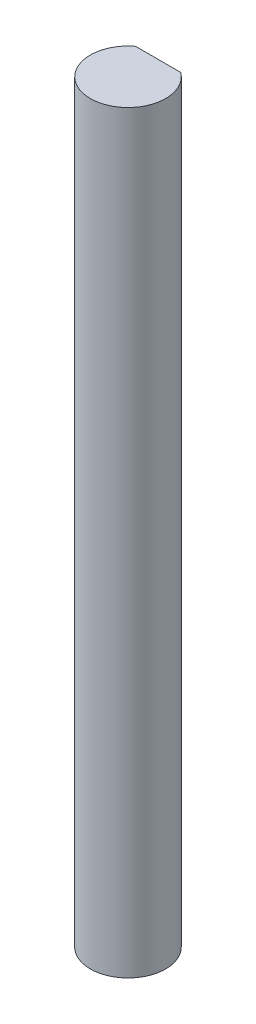
SolidWorks part; units mm, degrees
ref_plane "前视基准面" through (0, 0, 0) normal (0, 0, 1) x (1, 0, 0)
ref_plane "上视基准面" through (0, 0, 0) normal (0, 1, 0) x (1, 0, 0)
ref_plane "右视基准面" through (0, 0, 0) normal (1, 0, 0) x (0, 0, -1)
sketch "草图1" plane through (0, 0, 0) normal (0, 1, 0) x (1, 0, 0)
  line L0 (-1.5, 2) -> (1.5, 2)
  line L1 (0, 2) -> (0, -2.5) construction
  circle A0 centre (0, 0) radius 2.5
  dimension "D2" = 5
  dimension "D1" = 4.5
extrude "凸台-拉伸1" add sketch "草图1" along normal blind 50 contours L1 L0 A0 | L0 L1 A0
